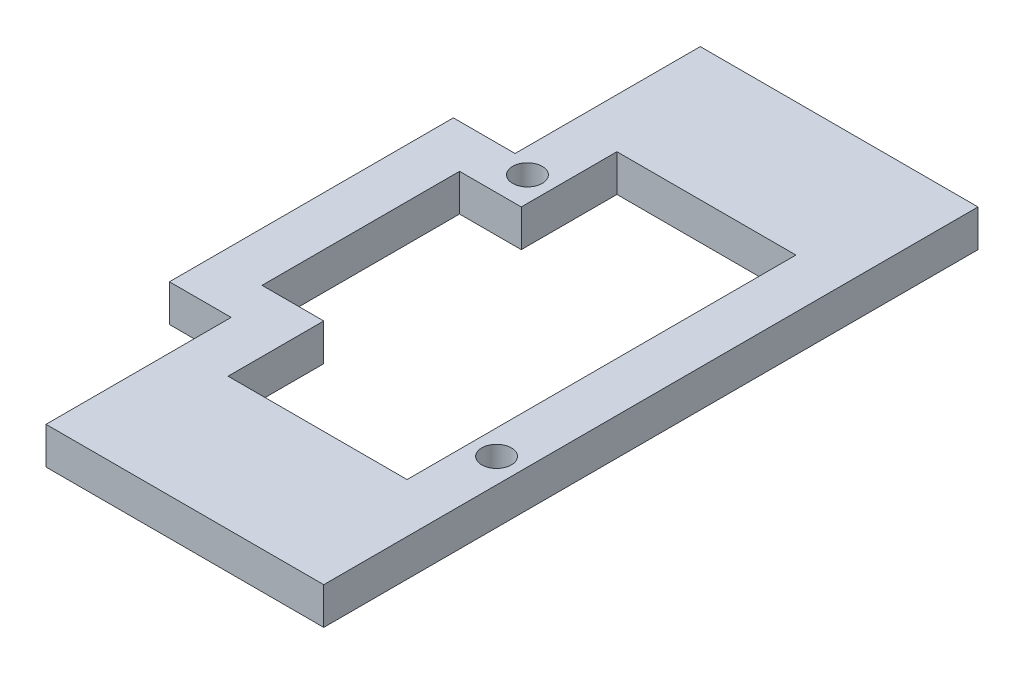
SolidWorks part; units mm, degrees
ref_plane "前视基准面" through (0, 0, 0) normal (0, 0, 1) x (1, 0, 0)
ref_plane "上视基准面" through (0, 0, 0) normal (0, 1, 0) x (1, 0, 0)
ref_plane "右视基准面" through (0, 0, 0) normal (1, 0, 0) x (0, 0, -1)
other "Configuration Table"
sketch "草图1" plane through (0, 0, 0) normal (0, 1, 0) x (1, 0, 0)
  line L10 (-9.7382, 66.9848) -> (35.2618, 66.9848)
  line L11 (-9.7382, 66.9848) -> (-9.7382, -39.0152)
  line L12 (-9.7382, -39.0152) -> (35.2618, -39.0152)
  line L13 (35.2618, 66.9848) -> (35.2618, -39.0152)
  line L14 (-1.7382, 45.4848) -> (27.2618, 45.4848)
  line L15 (-1.7382, 45.4848) -> (-1.7382, -17.5152)
  line L16 (-1.7382, -17.5152) -> (27.2618, -17.5152)
  line L17 (27.2618, 45.4848) -> (27.2618, -17.5152)
  line L18 (-9.7382, 36.9848) -> (-19.7382, 36.9848)
  line L19 (-9.7382, 36.9848) -> (-9.7382, -9.0152)
  line L20 (-9.7382, -9.0152) -> (-19.7382, -9.0152)
  line L21 (-19.7382, 36.9848) -> (-19.7382, -9.0152)
  line L22 (-1.7382, 29.9848) -> (-11.7382, 29.9848)
  line L23 (-1.7382, 29.9848) -> (-1.7382, -2.0152)
  line L24 (-1.7382, -2.0152) -> (-11.7382, -2.0152)
  line L25 (-11.7382, 29.9848) -> (-11.7382, -2.0152)
  circle A0 centre (-5.7382, 34.9848) radius 2.4
  circle A1 centre (31.2618, -7.0152) radius 2.4
  dimension "D1" = 4.8
  dimension "D2" = 4.8
  dimension "D3" = 30
  dimension "D4" = 30
  dimension "D5" = 10
  dimension "D6" = 7
  dimension "D7" = 7
  dimension "D8" = 10
extrude "凸台-拉伸1" add sketch "草图1" along normal blind 6 contours L15 L24 L11 L12 L13 L10 L22 L14 L17 L16 A1 A0 | L25 L22 L11 L18 L21 L20 L24
